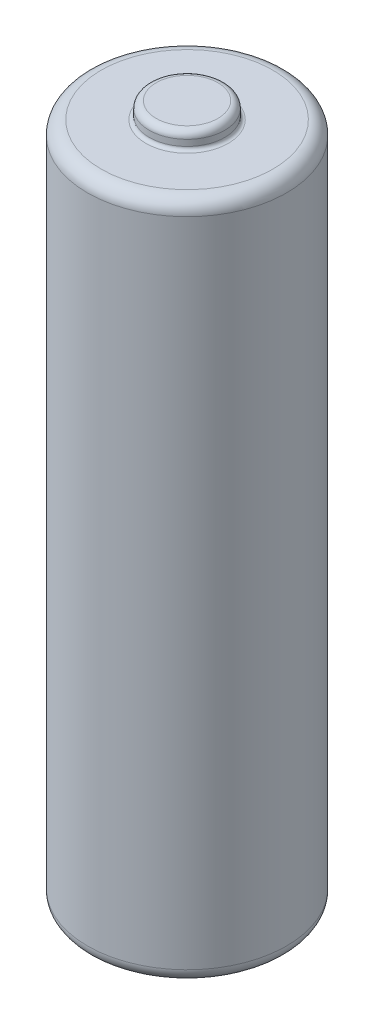
SolidWorks part; units mm, degrees
ref_plane "Front Plane" through (0, 0, 0) normal (0, 0, 1) x (1, 0, 0)
ref_plane "Top Plane" through (0, 0, 0) normal (0, 1, 0) x (1, 0, 0)
ref_plane "Right Plane" through (0, 0, 0) normal (1, 0, 0) x (0, 0, -1)
sketch "Sketch1" plane through (0, 0, 0) normal (0, 1, 0) x (1, 0, 0)
  circle A0 centre (0, 0) radius 7.25
extrude "Boss-Extrude4" add sketch "Sketch1" along normal blind 49.5
sketch "Sketch8" plane through (0, 49.5, 0) normal (0, 1, 0) x (1, 0, 0)
  circle A0 centre (0, 0) radius 2.75
extrude "Boss-Extrude5" add sketch "Sketch8" along normal blind 1.2
fillet "Fillet1" radius 1 2 edges at (0, 0, 7.25) (0, 49.5, 7.25)
fillet "Fillet3" radius 0.25 1 edges at (0, 49.5, 2.75)
fillet "Fillet4" radius 0.5 1 edges at (0, 50.7, 2.75)
